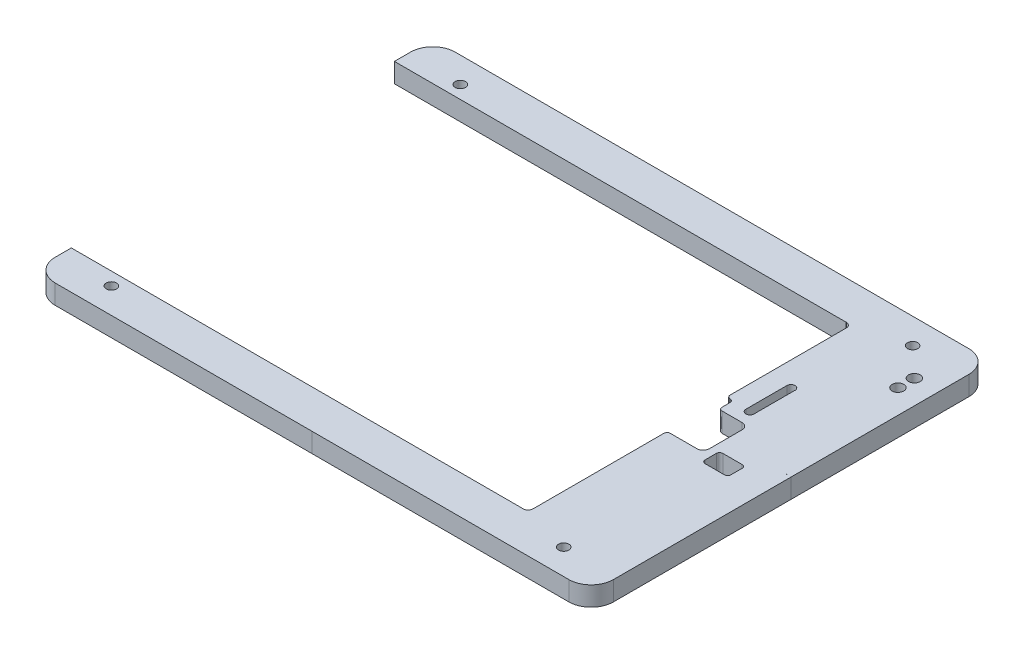
SolidWorks part; units mm, degrees
ref_plane "Ebene vorne" through (0, 0, 0) normal (0, 0, 1) x (1, 0, 0)
ref_plane "Ebene oben" through (0, 0, 0) normal (0, 1, 0) x (1, 0, 0)
ref_plane "Ebene rechts" through (0, 0, 0) normal (1, 0, 0) x (0, 0, -1)
sketch "Skizze1" plane through (0, 0, 0) normal (0, 1, 0) x (1, 0, 0)
  line L0 (69.5, -9.75) -> (75.5, -9.75)
  line L1 (69.5, -4.25) -> (75.5, -4.25)
  line L2 (76.5, -7) -> (76.5, -5.25)
  line L3 (76.5, -8.75) -> (76.5, -7)
  line L4 (68.5, -8.75) -> (68.5, -7)
  line L5 (68.5, -7) -> (68.5, -5.25)
  line L6 (-85, -55) -> (-85, -50)
  line L7 (57, 8) -> (57, 10.5)
  line L8 (55, 12.5) -> (55, 48.5)
  line L9 (58, 7) -> (64.25, 7)
  line L11 (55, -48.5) -> (55, -8)
  line L12 (56, -7) -> (64.25, -7)
  line L14 (63.77, 11.15) -> (63.77, 23.85)
  line L15 (61.23, 11.15) -> (61.23, 23.85)
  line L16 (-85, 50) -> (53.5, 50)
  line L17 (-85, -50) -> (53.5, -50)
  line L18 (-79.5, 60.5) -> (0.0001, 60.5)
  line L19 (-85, 50) -> (-85, 55)
  line L20 (85, 0) -> (85, 55)
  line L21 (0.0001, 60.5) -> (79.5, 60.5)
  line L22 (0, -60.5) -> (79.5, -60.5)
  line L23 (85, 0) -> (85, -55)
  line L24 (-79.5, -60.5) -> (0, -60.5)
  line L25 (-86.4, 50) -> (-86.4, 55)
  line L26 (-79.5, 61.9) -> (0.0001, 61.9)
  line L27 (0.0001, 61.9) -> (79.5, 61.9)
  line L28 (86.4, 0) -> (86.4, 55)
  line L29 (86.4, 0) -> (86.4, -55)
  line L30 (0, -61.9) -> (79.5, -61.9)
  line L31 (-79.5, -61.9) -> (0, -61.9)
  line L32 (-86.4, -55) -> (-86.4, -50)
  line L42 (-85, -50) -> (-86.4, -50)
  line L43 (66.17, 5.08) -> (66.25, 0) construction
  line L44 (66.17, -5.08) -> (66.25, 0) construction
  line L45 (66.17, 5.08) -> (66.17, -5.08)
  line L46 (-85, 50) -> (-86.4, 50)
  line L47 (-86.4, 48.6) -> (-86.4, 55) construction
  line L48 (55.6, 8) -> (55.6, 10.1336) construction
  line L49 (53.6, 12.5) -> (53.6, 48.5) construction
  line L50 (56, -5.6) -> (64.25, -5.6) construction
  line L51 (64.7699, -5.0725) -> (64.8498, 0) construction
  line L52 (64.7699, 5.0725) -> (64.8498, 0) construction
  line L53 (58, 5.6) -> (64.25, 5.6) construction
  line L54 (53.6, -48.5) -> (53.6, -8) construction
  line L55 (-86.4, 48.6) -> (53.5, 48.6) construction
  line L56 (-86.4, -48.6) -> (53.5, -48.6) construction
  line L57 (-86.4, -55) -> (-86.4, -48.6) construction
  circle A17 centre (55, 48.5) radius 0.0635
  circle A29 centre (63.77, 23.85) radius 0.0635
  circle A33 centre (53.5, 50) radius 0.0635
  circle A40 centre (85, 0) radius 0.0635
  circle A46 centre (85, 0) radius 0.0635
  arc A50 (76.5, -5.25) -> (75.5, -4.25) centre (75.5, -5.25) ccw
  arc A53 (75.5, -9.75) -> (76.5, -8.75) centre (75.5, -8.75) ccw
  arc A56 (68.5, -8.75) -> (69.5, -9.75) centre (69.5, -8.75) ccw
  arc A59 (69.5, -4.25) -> (68.5, -5.25) centre (69.5, -5.25) ccw
  arc A62 (57, 8) -> (58, 7) centre (58, 8) ccw
  arc A65 (57, 10.5) -> (56, 11.5) centre (56, 10.5) ccw
  arc A68 (55, 12.5) -> (56, 11.5) centre (56, 12.5) ccw
  arc A71 (66.17, 5.08) -> (64.25, 7) centre (64.25, 5.08) ccw
  arc A74 (56, -7) -> (55, -8) centre (56, -8) ccw
  arc A77 (64.25, -7) -> (66.17, -5.08) centre (64.25, -5.08) ccw
  arc A80 (61.23, 11.15) -> (63.77, 11.15) centre (62.5, 11.15) ccw
  arc A83 (63.77, 23.85) -> (61.23, 23.85) centre (62.5, 23.85) ccw
  circle A85 centre (63.77, 23.85) radius 0.0635
  circle A86 centre (79, 40.46) radius 1.8
  circle A89 centre (79, 45.54) radius 1.8
  arc A92 (55, 48.5) -> (53.5, 50) centre (53.5, 48.5) ccw
  circle A93 centre (53.5, 50) radius 0.0635
  circle A94 centre (55, 48.5) radius 0.0635
  arc A95 (53.5, -50) -> (55, -48.5) centre (53.5, -48.5) ccw
  circle A98 centre (-70, -54) radius 1.6
  circle A101 centre (70, -54) radius 1.6
  circle A104 centre (70, 54) radius 1.6
  circle A107 centre (-70, 54) radius 1.6
  arc A110 (-79.5, 60.5) -> (-85, 55) centre (-79.5, 55) ccw
  arc A113 (85, 55) -> (79.5, 60.5) centre (79.5, 55) ccw
  arc A116 (79.5, -60.5) -> (85, -55) centre (79.5, -55) ccw
  arc A119 (-85, -55) -> (-79.5, -60.5) centre (-79.5, -55) ccw
  arc A122 (-79.5, 61.9) -> (-86.4, 55) centre (-79.5, 55) ccw
  arc A123 (86.4, 55) -> (79.5, 61.9) centre (79.5, 55) ccw
  arc A124 (79.5, -61.9) -> (86.4, -55) centre (79.5, -55) ccw
  arc A125 (-86.4, -55) -> (-79.5, -61.9) centre (-79.5, -55) ccw
  arc A134 (55.6, 8) -> (58, 5.6) centre (58, 8) ccw construction
  arc A135 (55.6, 10.1336) -> (55.6, 10.1336) centre (55.6, 10.1336) ccw construction
  arc A136 (53.6, 12.5) -> (55.6, 10.1336) centre (56, 12.5) ccw construction
  arc A137 (64.25, -5.6) -> (64.7699, -5.0725) centre (64.25, -5.08) ccw construction
  arc A138 (64.7699, 5.0725) -> (64.25, 5.6) centre (64.25, 5.08) ccw construction
  arc A139 (56, -5.6) -> (53.6, -8) centre (56, -8) ccw construction
  arc A140 (53.6, 48.5) -> (53.5, 48.6) centre (53.5, 48.5) ccw construction
  arc A141 (53.5, -48.6) -> (53.6, -48.5) centre (53.5, -48.5) ccw construction
  dimension "D1" = 1.4
extrude "Aufsatz-Linear austragen1" add sketch "Skizze1" along normal blind 6 contours L6 A119 L24 L22 A116 L23 A40 L20 A113 L21 L18 A110 L19 L16 A33 A92 A17 L8 A68 A65 L7 A62 L9 A71 L45 A77 L12 A74 L11 A95 L17 A59 L1 A50 L2 L3 A53 L0 A56 L4 L5 A83 A29 L14 A80 L15 A86 | L32 A125 L31 L30 A124 L29 L28 A123 L27 L26 A122 L25 L46 L19 A110 L18 L21 A113 L20 A40 L23 A116 L22 L24 A119 L6 L42
